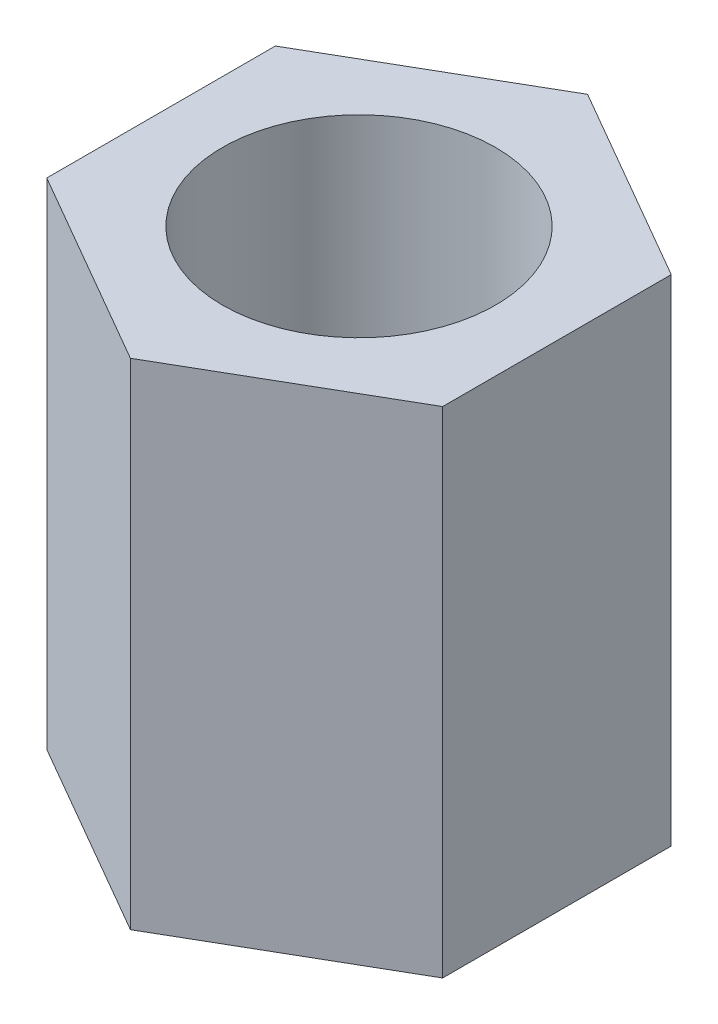
SolidWorks part; units mm, degrees
ref_plane "Front Plane" through (0, 0, 0) normal (0, 0, 1) x (1, 0, 0)
ref_plane "Top Plane" through (0, 0, 0) normal (0, 1, 0) x (1, 0, 0)
ref_plane "Right Plane" through (0, 0, 0) normal (1, 0, 0) x (0, 0, -1)
sketch "Sketch1" plane through (0, 0, 0) normal (0, 1, 0) x (1, 0, 0)
  line L1 (0, 2.9329) -> (-2.54, 1.4665)
  line L2 (-2.54, 1.4665) -> (-2.54, -1.4665)
  line L3 (-2.54, -1.4665) -> (0, -2.9329)
  line L4 (0, -2.9329) -> (2.54, -1.4665)
  line L5 (2.54, -1.4665) -> (2.54, 1.4665)
  line L6 (2.54, 1.4665) -> (0, 2.9329)
  circle A0 centre (0, 0) radius 2.54 construction
  circle A1 centre (0, 0) radius 1.7526
  dimension "D1" = 5.08
  dimension "D2" = 3.5052
extrude "Boss-Extrude1" add sketch "Sketch1" along normal blind 6.35
